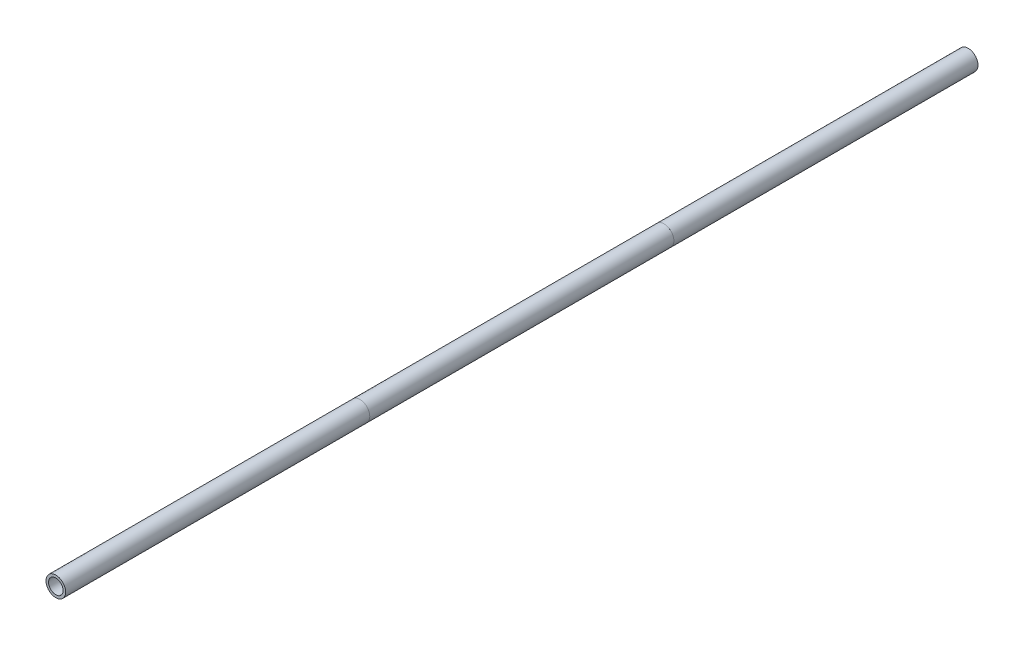
SolidWorks part; units mm, degrees
ref_plane "Front Plane" through (0, 0, 0) normal (0, 0, 1) x (1, 0, 0)
ref_plane "Top Plane" through (0, 0, 0) normal (0, 1, 0) x (1, 0, 0)
ref_plane "Right Plane" through (0, 0, 0) normal (1, 0, 0) x (0, 0, -1)
sketch "Sketch1" plane through (0, 0, 0) normal (0, 0, 1) x (1, 0, 0)
  circle A0 centre (0, 0) radius 10.668
  dimension "Pipe OD" = 21.336
extrude "Extrude-Thin1" add sketch "Sketch1" along normal mid plane 330 thin thin type one direction reverse wall 2.7686
sketch "Sketch2" plane through (0, 0, 165) normal (0, 0, 1) x (1, 0, 0)
  circle A0 centre (0, 0) radius 7.8994
  circle A1 centre (0, 0) radius 10.668
  circle A2 centre (0, 0) radius 7.8994 construction
  circle A3 centre (0, 0) radius 10.668 construction
extrude "Boss-Extrude2" add sketch "Sketch2" along normal blind 330 separate body
sketch "Sketch3" plane through (0, 0, -165) normal (0, 0, -1) x (-1, 0, 0)
  circle A0 centre (0, 0) radius 10.668
  circle A1 centre (0, 0) radius 7.8994
  circle A2 centre (0, 0) radius 7.8994 construction
  circle A3 centre (0, 0) radius 10.668 construction
extrude "Boss-Extrude3" add sketch "Sketch3" along normal blind 330 separate body
